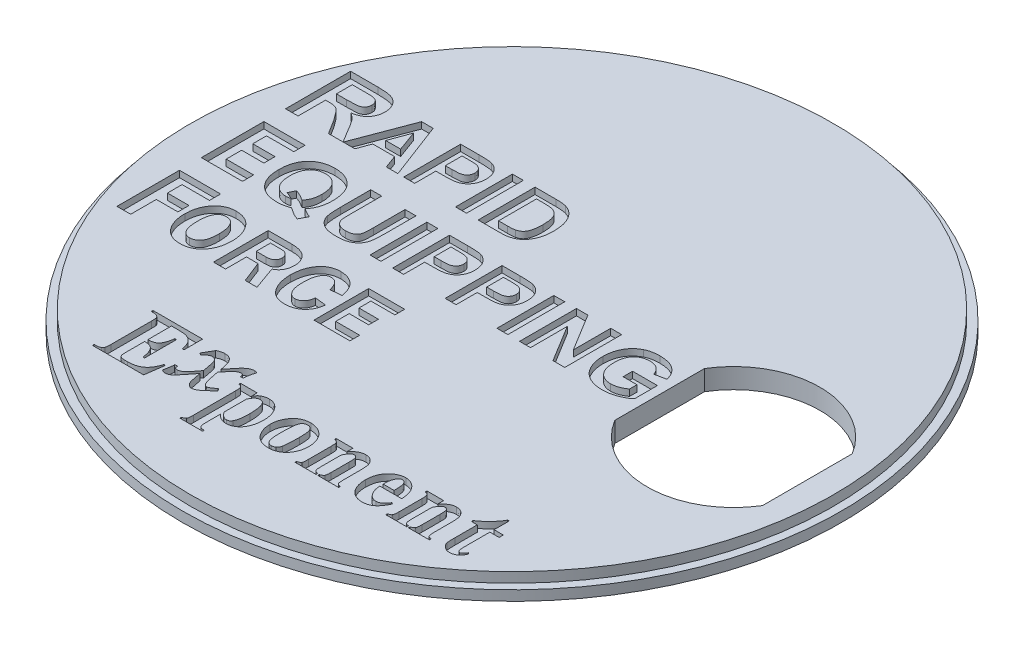
SolidWorks part; units mm, degrees
material "6061 Alloy"
ref_plane "Front Plane" through (0, 0, 0) normal (0, 0, 1) x (1, 0, 0)
ref_plane "Top Plane" through (0, 0, 0) normal (0, 1, 0) x (1, 0, 0)
ref_plane "Right Plane" through (0, 0, 0) normal (1, 0, 0) x (0, 0, -1)
sketch "Sketch1" plane through (0, 0, 0) normal (0, 1, 0) x (1, 0, 0)
  circle A0 centre (0, 0) radius 20.828
  dimension "D1" = 41.656
extrude "Boss-Extrude1" add sketch "Sketch1" along normal blind 1.27
sketch "Sketch2" plane through (0, 1.27, 0) normal (0, 1, 0) x (1, 0, 0)
  circle A0 centre (0, 0) radius 20.32
  circle A1 centre (0, 0) radius 20.828
  circle A2 centre (0, 0) radius 20.828 construction
  dimension "D1" = 0.508
extrude "Cut-Extrude2" cut sketch "Sketch2" against normal blind 0.635
sketch "Sketch3" plane through (0, 1.27, 0) normal (0, 1, 0) x (1, 0, 0)
  line L0 (20.828, 3.7545) -> (20.828, -12.2477) construction
  line L1 (0, 0) -> (20.828, 0) construction
  line L2 (18.6677, 2.8354) -> (18.6677, -2.8354)
  line L3 (9.3332, 2.8354) -> (9.3332, -2.8354)
  arc A0 (9.3332, -2.8354) -> (18.6677, -2.8354) centre (14.0005, 0) ccw
  circle A1 centre (0, 0) radius 20.828 construction
  arc A2 (18.6677, 2.8354) -> (9.3332, 2.8354) centre (14.0005, 0) ccw
  dimension "D1" = 10.922
  dimension "D3" = 4.6672
  dimension "D2" = 14.0005
extrude "Cut-Extrude3" cut sketch "Sketch3" against normal through all
sketch "Sketch12" plane through (0, 0, 0) normal (0, -1, 0) x (1, 0, 0)
  line L1 (-7.6581, 18.2626) -> (5.6769, 18.2626)
  line L2 (-9.2456, 16.6751) -> (-9.2456, 3.3401)
  line L3 (-7.6581, 1.7526) -> (5.6769, 1.7526)
  line L4 (7.2644, 16.6751) -> (7.2644, 3.3401)
  line L5 (-9.2456, 18.2626) -> (7.2644, 1.7526) construction
  line L6 (-9.2456, 1.7526) -> (7.2644, 18.2626) construction
  arc A0 (-9.2456, 16.6751) -> (-7.6581, 18.2626) centre (-7.6581, 16.6751) cw
  arc A1 (-7.6581, 1.7526) -> (-9.2456, 3.3401) centre (-7.6581, 3.3401) cw
  arc A2 (7.2644, 3.3401) -> (5.6769, 1.7526) centre (5.6769, 3.3401) cw
  arc A3 (7.2644, 16.6751) -> (5.6769, 18.2626) centre (5.6769, 16.6751) ccw
  point P0 (-0.9906, 10.0076)
  dimension "D3" = 16.51
  dimension "D4" = 1.5875
  dimension "D1" = 10.0076
  dimension "D2" = 0.9906
extrude "Cut-Extrude4" cut sketch "Sketch12" against normal blind 0.508
sketch "Sketch13" plane through (0, 0, 0) normal (0, -1, 0) x (1, 0, 0)
  line L0 (-13.1479, -13.7739) -> (-10.5519, -15.8507)
  line L1 (-16.7984, -13.2341) -> (-6.871, -21.176) construction
  line L2 (-13.0111, -16.2639) -> (0, 0) construction
  arc A0 (-10.5519, -15.8507) -> (-13.1479, -13.7739) centre (-10.16, -12.7) ccw
  circle A1 centre (0, 0) radius 20.828 construction
  dimension "D3" = 6.35
  dimension "D4" = 2.7051
  dimension "D1" = 12.7
  dimension "D2" = 10.16
sketch "Sketch14" plane through (0, 1.27, 0) normal (0, 1, 0) x (1, 0, 0)
  line L0 (-18.542, 3.81) -> (-18.542, -1.524) construction
  line L1 (-18.542, -1.524) -> (-18.542, -6.858) construction
  text T0 "R" font "Arial" height in points 16
  text T1 "E" font "Franklin Gothic Medium" height in points 16
  text T2 "F" font "Franklin Gothic Medium" height in points 16
  text T3 "APID" font "Arial" height in points 14
  text T4 "QUIPPING" font "Arial" height in points 14
  text T5 "ORCE" font "Franklin Gothic Medium" height in points 14
  text T6 "E  ponent" font "Times New Roman" height in points 16
  text T7 "x" font "Palatino Linotype" height in points 16
  dimension "D1" = 4.064
  dimension "D2" = 5.334
  dimension "D3" = 18.542
  dimension "D4" = 3.81
  dimension "D5" = 3.302
  dimension "D6" = 2.794
  dimension "D7" = 11.43
  dimension "D8" = 15.24
  dimension "D9" = 3.81
  dimension "D10" = 0.889
extrude "Cut-Extrude5" cut sketch "Sketch14" against normal offset from surface (0.4064 mm away) 0.3556 up to face at (-0.9906, 0.508, 10.0076)
